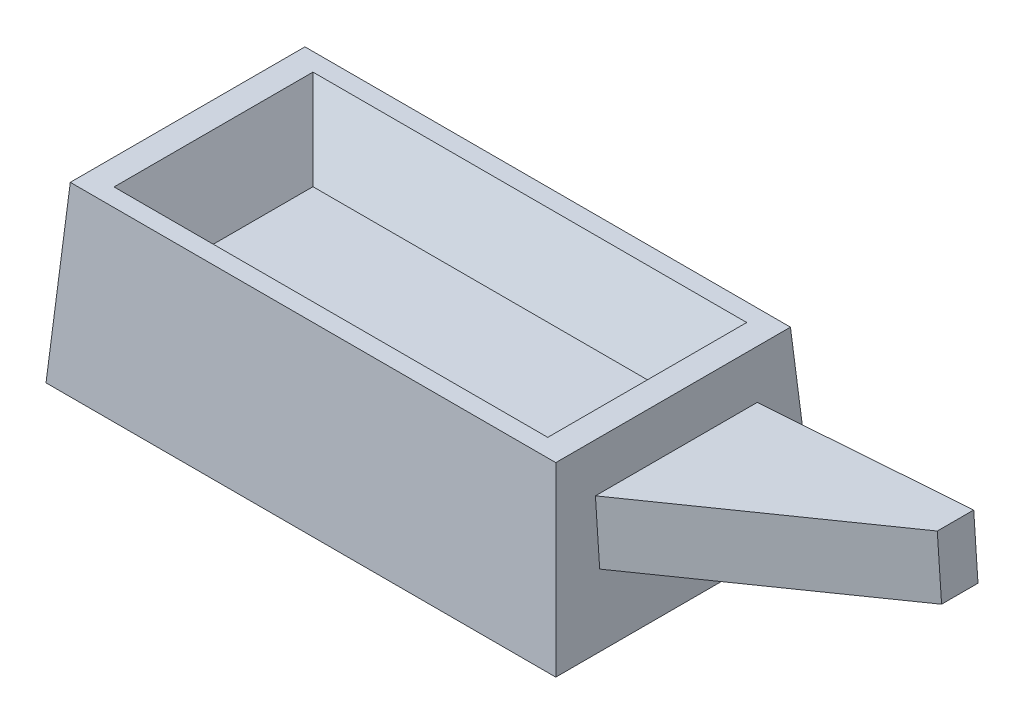
SolidWorks part; units mm, degrees
ref_plane "Front Plane" through (0, 0, 0) normal (0, 0, 1) x (1, 0, 0)
ref_plane "Top Plane" through (0, 0, 0) normal (0, 1, 0) x (1, 0, 0)
ref_plane "Right Plane" through (0, 0, 0) normal (1, 0, 0) x (0, 0, -1)
sketch "Sketch1" plane through (0, 0, 0) normal (0, 1, 0) x (1, 0, 0)
  line L1 (-102.8928, -52.2674) -> (102.8928, -52.2674)
  line L2 (-102.8928, -52.2674) -> (-102.8928, 52.2674)
  line L3 (-102.8928, 52.2674) -> (102.8928, 52.2674)
  line L4 (102.8928, -52.2674) -> (102.8928, 52.2674)
  line L5 (-102.8928, -52.2674) -> (102.8928, 52.2674) construction
  line L6 (-102.8928, 52.2674) -> (102.8928, -52.2674) construction
  point P0 (0, 0)
extrude "Boss-Extrude1" add sketch "Sketch1" along normal blind 70.104 draft 4
sketch "Sketch2" plane through (0, 70.104, 0) normal (0, 1, 0) x (1, 0, 0)
  line L1 (-72.8794, -25.487) -> (72.8794, -25.487)
  line L2 (-72.8794, -25.487) -> (-72.8794, 25.487)
  line L3 (-72.8794, 25.487) -> (72.8794, 25.487)
  line L4 (72.8794, -25.487) -> (72.8794, 25.487)
  line L5 (-72.8794, -25.487) -> (72.8794, 25.487) construction
  line L6 (-72.8794, 25.487) -> (72.8794, -25.487) construction
  point P0 (0, 0)
extrude "Cut-Extrude1" cut sketch "Sketch2" against normal blind 25.4
sketch "Sketch3" plane through (102.3922, 7.16, 0) normal (0.9976, 0.0698, 0) x (0, 0, -1)
  line L1 (-32.6491, 19.9219) -> (32.6491, 19.9219)
  line L2 (-32.6491, 19.9219) -> (-32.6491, 44.7216)
  line L3 (-32.6491, 44.7216) -> (32.6491, 44.7216)
  line L4 (32.6491, 19.9219) -> (32.6491, 44.7216)
  line L5 (-32.6491, 19.9219) -> (32.6491, 44.7216) construction
  line L6 (-32.6491, 44.7216) -> (32.6491, 19.9219) construction
  point P0 (0, 32.3218)
extrude "Boss-Extrude2" add sketch "Sketch3" along normal blind 87.63
draft "Draft1" type of draft neutral plane draft angle 30 faces to draft 4 face at (0, 57.404, 25.487) face at (72.8794, 57.404, 0) face at (0, 57.404, -25.487) face at (-72.8794, 57.404, 0) neutral plane through (0, 44.704, 0) neutral plane normal (0, 1, 0) parameters "D1"=30
draft "Draft2" type of draft neutral plane draft angle 30 faces to draft 1 face at (143.8458, 42.4594, 32.6491) neutral plane through (102.8928, 0, 52.2674) neutral plane normal (0.9976, 0.0698, 0) parameters "D1"=30
